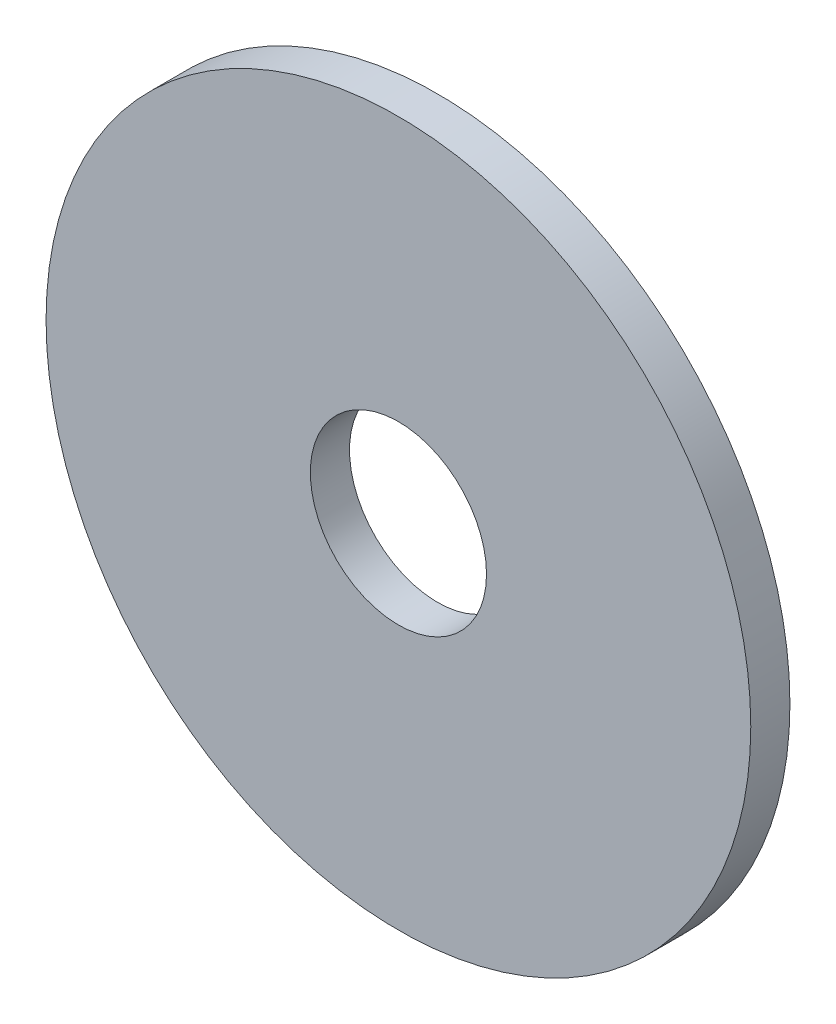
SolidWorks part; units mm, degrees
ref_plane "Front Plane" through (0, 0, 0) normal (1, 0, 0) x (0, 1, 0)
ref_plane "Top Plane" through (0, 0, 0) normal (0, 0, 1) x (0, 1, 0)
ref_plane "Right Plane" through (0, 0, 0) normal (0, 1, 0) x (-1, 0, 0)
sketch "Sketch1" plane through (0, 0, 0) normal (0, 0, 1) x (0, 1, 0)
  circle A0 centre (0, 0) radius 9
  circle A1 centre (0, 0) radius 2.25
  dimension "D1" = 18
  dimension "D2" = 4.5
extrude "Boss-Extrude1" add sketch "Sketch1" along normal mid plane 1
